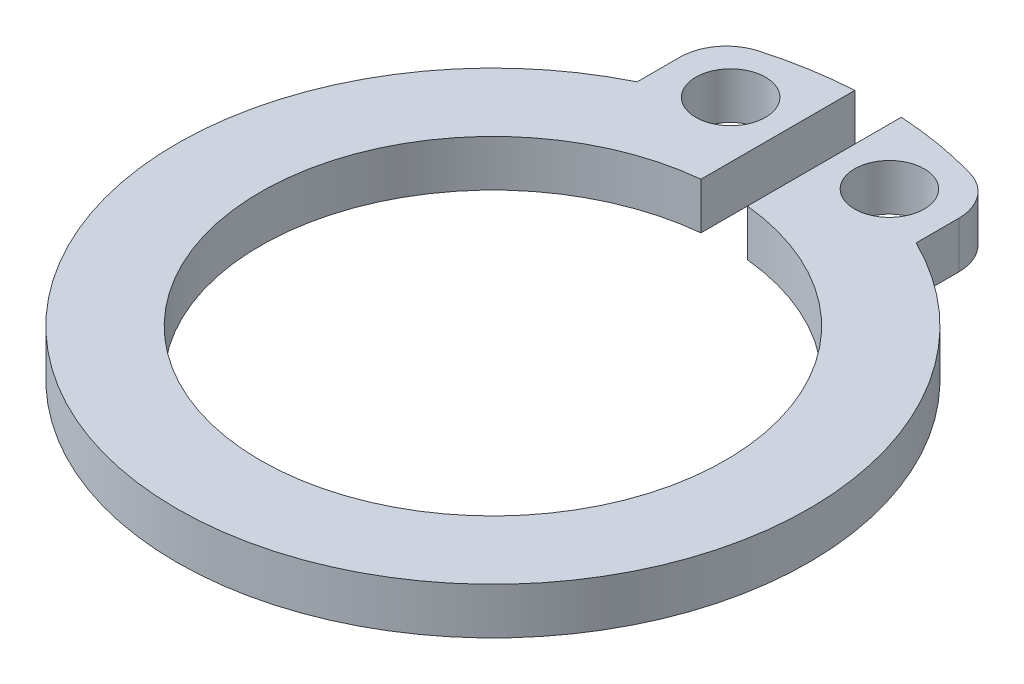
SolidWorks part; units mm, degrees
ref_plane "Front Plane" through (0, 0, 0) normal (0, 0, 1) x (1, 0, 0)
ref_plane "Top Plane" through (0, 0, 0) normal (0, 1, 0) x (1, 0, 0)
ref_plane "Right Plane" through (0, 0, 0) normal (1, 0, 0) x (0, 0, -1)
sketch "Sketch1" plane through (0, 0, 0) normal (0, 1, 0) x (1, 0, 0)
  circle A0 centre (0, 0) radius 5
  circle A1 centre (0, 0) radius 6.8
  dimension "D1" = 10
  dimension "D2" = 1.8
extrude "Boss-Extrude1" add sketch "Sketch1" along normal blind 1
sketch "Sketch2" plane through (0, 0, 0) normal (0, -1, 0) x (1, 0, 0)
  line L0 (3, -7.7389) -> (3, -6.1025)
  line L1 (0.5, -8.2849) -> (0.5, -6.7816)
  line L2 (0, 0) -> (0, -13.8447) construction
  line L3 (-0.5, -8.2849) -> (-0.5, -6.7816)
  line L4 (-3, -7.7389) -> (-3, -6.1025)
  arc A0 (0.5, -8.2849) -> (3, -7.7389) centre (0, 0) ccw
  circle A1 centre (0, 0) radius 5 construction
  circle A2 centre (0, 0) radius 6.8 construction
  arc A3 (0.5, -6.7816) -> (3, -6.1025) centre (0, 0) ccw
  arc A4 (-0.5, -6.7816) -> (-3, -6.1025) centre (0, 0) cw
  arc A5 (-0.5, -8.2849) -> (-3, -7.7389) centre (0, 0) cw
  dimension "D1" = 3.3
  dimension "D2" = 0.5
  dimension "D3" = 3
extrude "Boss-Extrude2" add sketch "Sketch2" against normal up to surface (1 mm away) up to face at (0, 1, 6.8)
fillet "Fillet1" radius 1 2 edges at (-3, 0.5, -7.7389) (3, 0.5, -7.7389)
sketch "Sketch3" plane through (0, 0, 0) normal (0, -1, 0) x (1, 0, 0)
  line L1 (-0.5, -4.9749) -> (0.5, -4.9749)
  line L2 (-0.5, -4.9749) -> (-0.5, -8.2849)
  line L3 (-0.5, -8.2849) -> (0.5, -8.2849)
  line L4 (0.5, -4.9749) -> (0.5, -8.2849)
  circle A0 centre (0, 0) radius 5 construction
  point P7 (-0.5, -8.2849)
extrude "Cut-Extrude1" cut sketch "Sketch3" against normal through all
sketch "Sketch4" plane through (0, 0, 0) normal (0, -1, 0) x (1, 0, 0)
  line L0 (0, 0) -> (0, -2.1723) construction
  circle A0 centre (1.7077, -6.821) radius 0.75
  circle A1 centre (-1.7077, -6.821) radius 0.75
  dimension "D1" = 1.5
extrude "Cut-Extrude2" cut sketch "Sketch4" against normal through all
